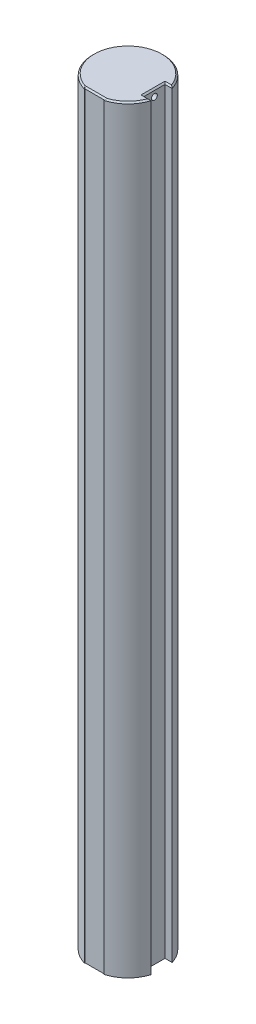
SolidWorks part; units mm, degrees
ref_plane "Plan de face" through (0, 0, 0) normal (0, 0, 1) x (1, 0, 0)
ref_plane "Plan de dessus" through (0, 0, 0) normal (0, 1, 0) x (1, 0, 0)
ref_plane "Plan de droite" through (0, 0, 0) normal (1, 0, 0) x (0, 0, -1)
sketch "Esquisse1" plane through (0, 0, 0) normal (0, 1, 0) x (1, 0, 0)
  circle A0 centre (0, 0) radius 20
  dimension "D1" = 40
extrude "Boss.-Extru.1" add sketch "Esquisse1" along normal blind 430.4
hole_wizard "Trou taraudé M81" positions "Esquisse6" profile "Esquisse7" tap size "M8" standard "DIN"
sketch "Esquisse6" plane through (0, 0, 0) normal (0, -1, 0) x (-1, 0, 0)
  line L0 (0, -12.5) -> (0, 12.5) construction
  point P0 (0, -12.5)
  point P3 (0, 12.5)
  dimension "D1" = 25
sketch "Esquisse7" plane through (0, 0, 12.5) normal (1, 0, 0) x (0, 0, -1)
  line L0 (0, 0) -> (0, 24.2929)
  line L1 (0, 24.2929) -> (3.4, 22.25)
  line L2 (3.4, 22.25) -> (3.4, 0)
  line L5 (3.4, 0) -> (0, 0)
  line L10 (0, 24.2929) -> (-3.4, 22.25) construction
  line L11 (0, -6.35) -> (0, 107.95) construction
  dimension "Diamètre du trou pour taraudage" = 6.8
  dimension "Profondeur du trou pour taraudage" = 22.25
  dimension "Angle de pointe" = 118
cosmetic thread "Filetage de perçage2" parameters "D1"=16, "D2"=8
cosmetic thread "Filetage de perçage3" parameters "D1"=16, "D2"=8
sketch "Esquisse8" plane through (0, 0, 0) normal (0, -1, 0) x (1, 0, 0)
  line L0 (-5.5, 19.2289) -> (-5.5, 18.9)
  line L1 (-5.5, 18.9) -> (5.5, 18.9)
  line L2 (5.5, 18.9) -> (5.5, 19.2289)
  line L3 (19.0788, 6) -> (15, 6)
  line L4 (15, 6) -> (15, -6)
  line L5 (15, -6) -> (19.0788, -6)
  line L6 (19.0788, 6) -> (20, 6) construction
  line L7 (20, 6) -> (20, -6) construction
  line L8 (20, -6) -> (19.0788, -6) construction
  line L9 (-5.5, 19.2289) -> (-5.5, 20) construction
  line L10 (-5.5, 20) -> (5.5, 20) construction
  line L11 (5.5, 20) -> (5.5, 19.2289) construction
  circle A0 centre (0, 0) radius 20 construction
  arc A1 (5.5, 19.2289) -> (-5.5, 19.2289) centre (0, 0) ccw
  arc A2 (19.0788, -6) -> (19.0788, 6) centre (0, 0) ccw
  dimension "D1" = 5
  dimension "D2" = 12
  dimension "D3" = 2.2
  dimension "D4" = 11
extrude "Enlèv. mat.-Extru.1" cut sketch "Esquisse8" against normal up to next and the other way through all
hole_wizard "Trou taraudé M41" positions "Esquisse9" profile "Esquisse10" tap size "M4" standard "DIN"
sketch "Esquisse9" plane through (15, 0, 0) normal (1, 0, 0) x (0, 0, -1)
  line L0 (0, 430.4) -> (0, 426.4) construction
  line L1 (-6, 430.4) -> (6, 430.4) construction
  point P0 (0, 426.4)
  dimension "D1" = 4
sketch "Esquisse10" plane through (15, 426.4, 0) normal (0, 1, 0) x (0, 0, -1)
  line L0 (0, 0) -> (0, 12.4914)
  line L1 (0, 12.4914) -> (1.65, 11.5)
  line L2 (1.65, 11.5) -> (1.65, 0)
  line L5 (1.65, 0) -> (0, 0)
  line L10 (0, 12.4914) -> (-1.65, 11.5) construction
  line L11 (0, -6.35) -> (0, 107.95) construction
  dimension "Diamètre du trou pour taraudage" = 3.3
  dimension "Profondeur du trou pour taraudage" = 11.5
  dimension "Angle de pointe" = 118
cosmetic thread "Filetage de perçage5" parameters "D1"=8, "D2"=4
chamfer "Chanfrein1" distance 0.8 angle 45 8 edges at (5.5, 430.4, 19.0644) (0, 430.4, 18.9) (-5.5, 430.4, 19.0644) (-14.3255, 430.4, -13.9564) (17.0394, 430.4, -6) (15, 430.4, 0) (17.0394, 430.4, 6) (13.9564, 430.4, 14.3255)
equation "\"r\"= 20"
equation "\"D1@Esquisse1\"=2*\"r\""
equation "\"chanfrein\"= 0.8"
equation "\"hauteurReglet\"= 400"
equation "\"BBD\"= 43.40"
equation "\"FFD\"= 17.5"
equation "\"margeReglet\"= 3.7"
equation "\"h\"= \"hauteurReglet\" + \"BBD\" - \"FFD\" + \"margeReglet\" + \"chanfrein\""
equation "\"D1@Boss.-Extru.1\"=\"h\""
equation "\"D1@Chanfrein1\"=\"chanfrein\""
